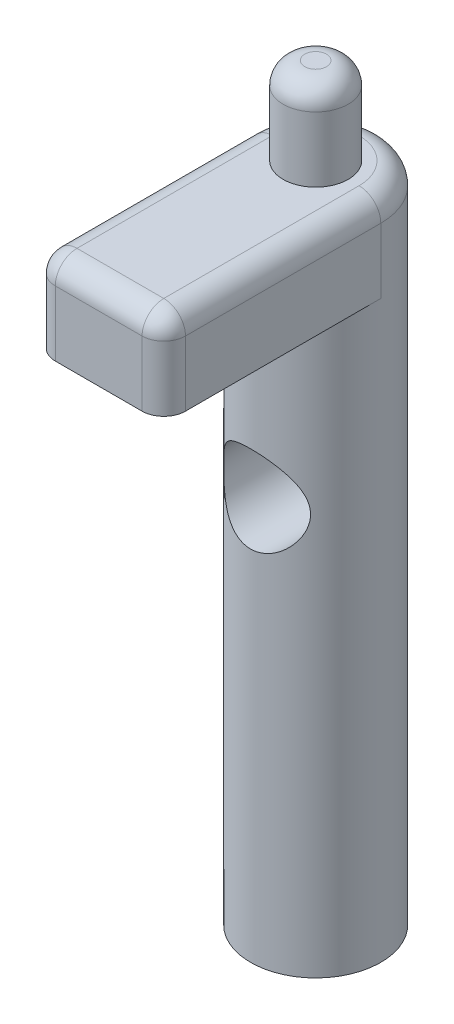
SolidWorks part; units mm, degrees
ref_plane "Front Plane" through (0, 0, 0) normal (0, 0, 1) x (1, 0, 0)
ref_plane "Top Plane" through (0, 0, 0) normal (0, 1, 0) x (1, 0, 0)
ref_plane "Right Plane" through (0, 0, 0) normal (1, 0, 0) x (0, 0, -1)
sketch "Sketch2" plane through (0, 0, 0) normal (0, 1, 0) x (1, 0, 0)
  circle A0 centre (0, 0) radius 3
  dimension "D1" = 6
extrude "Boss-Extrude1" add sketch "Sketch2" along normal blind 25
sketch "Sketch4" plane through (0, 25, 0) normal (0, 1, 0) x (1, 0, 0)
  line L2 (-3, 0) -> (-3, -10)
  line L3 (-3, -10) -> (3, -10)
  line L4 (3, 0) -> (3, -10)
  circle A2 centre (0, 0) radius 3 construction
  arc A3 (-3, 0) -> (3, 0) centre (0, 0) ccw
  point P0 (0, 0)
  dimension "D1" = 10
  dimension "D2" = 6
  dimension "D3" = 10
extrude "Boss-Extrude2" add sketch "Sketch4" along normal blind 4 separate body
sketch "Sketch5" plane through (0, 25, 0) normal (0, 1, 0) x (1, 0, 0)
  circle A0 centre (0, 0) radius 3 construction
  circle A1 centre (0, 0) radius 3
extrude "Boss-Extrude3" add sketch "Sketch5" along normal blind 4
fillet "Fillet1" radius 1 6 edges at (0, 29, -3) (3, 29, 5) (-3, 29, 5) (-3, 27, 10) (3, 27, 10) (0, 29, 10)
sketch "Sketch6" plane through (0, 0, 0) normal (0, 0, 1) x (1, 0, 0)
  line L0 (-3, 0) -> (3, 0) construction
  line L1 (-3, 0) -> (3, 0) construction
  line L2 (-3, 25) -> (3, 25) construction
  line L3 (-3, 25) -> (3, 25) construction
  line L4 (0, 25) -> (0, 17) construction
  circle A0 centre (0, 17) radius 2
  dimension "D2" = 4
  dimension "D1" = 8
extrude "Cut-Extrude1" cut sketch "Sketch6" against normal blind 4 and the other way blind 4
sketch "Sketch7" plane through (0, 29, 0) normal (0, 1, 0) x (1, 0, 0)
  circle A0 centre (0, 0) radius 1.5
  dimension "D1" = 3
extrude "Boss-Extrude4" add sketch "Sketch7" along normal blind 4 contours A0
fillet "Fillet2" radius 1 1 edges at (0, 33, 1.5)
sketch "Sketch8" plane through (0, 0, 0) normal (0, -1, 0) x (-1, 0, 0)
  circle A0 centre (0, 0) radius 3
  dimension "D1" = 6
extrude "Boss-Extrude5" add sketch "Sketch8" along normal blind 1.5
